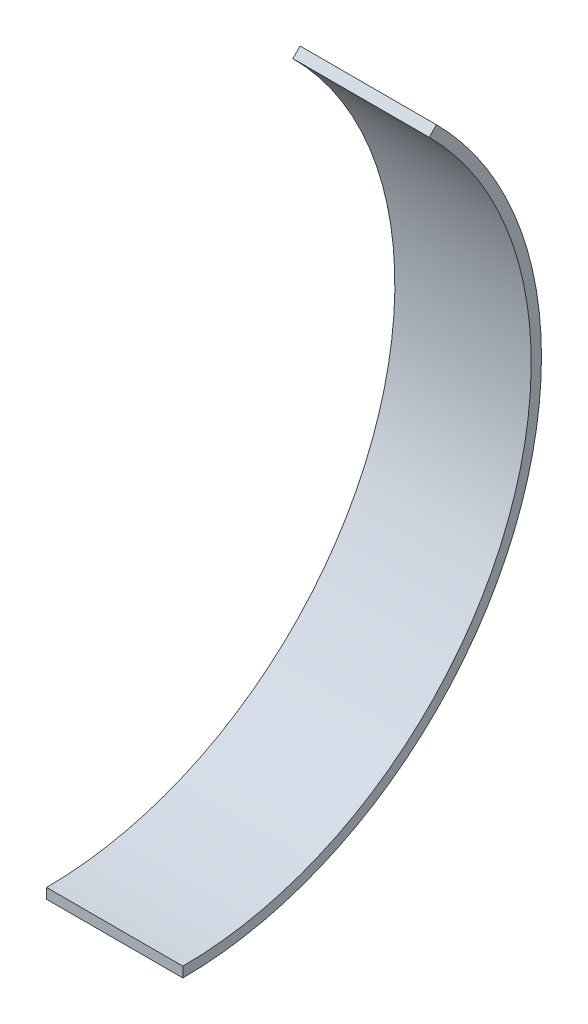
SolidWorks part; units mm, degrees
ref_plane "Front Plane" through (0, 0, 0) normal (0, 0, 1) x (1, 0, 0)
ref_plane "Top Plane" through (0, 0, 0) normal (0, 1, 0) x (1, 0, 0)
ref_plane "Right Plane" through (0, 0, 0) normal (1, 0, 0) x (0, 0, -1)
sketch "Sketch1" plane through (0, 0, 0) normal (0, 0, 1) x (1, 0, 0)
  line L0 (0, 0) -> (43.842, 0)
  line L1 (0, 112.014) -> (26.162, 112.014) construction
  dimension "D1" = 43.842
  dimension "D2" = 112.014
revolve "Revolve-Thin1" add sketch "Sketch1" angle 135 about L1
equation "\"FoamCore\" = \".2\""
equation "\"MDF\" = \".2\""
equation "\"GMaterial\"= \".2\""
equation "\"PVCMountDiameter\" = \"0.5in\""
equation "\"PVCMountDistanceToEdge\" = \"0.5\""
equation "\"PVCThickness\" = \"0.13in\""
equation "\"PVCDiameter\" = 1.5in"
equation "\"BaseWidth\" = \"8in\""
equation "\"BaseLength\" = \"10in\""
equation "\"BallDiameter\" = \"38mm\""
equation "\"BaseGap\" = \"4in\""
equation "\"FunnelTopDiameter\" = \"8in\""
equation "\"FunnelTopDepth\" = \"0.5in\""
equation "\"BallGap\" = \"0.1in\""
equation "\"FunnelLength\" = 3in"
equation "\"FunnelMaterial\" = 0.1in"
equation "\"FunnelLowerDiameter\" = 1.9in"
equation "\"FunnelDepth\" = 1.5in"
equation "\"FunnelBendLength\" = 2*pi*\"FunnelLowerDiameter\"/2*135"
equation "\"AmmoFeederLength\" = 1.5in + 76mm"
equation "\"WheelThickness\" = 0.5in"
equation "\"LauncherWheelDiameter\" = 76mm"
equation "\"MotorFrontLength\" = 0.95in"
equation "\"MotorBodyTotalLength\" = 2.03in"
equation "\"MotorFrontDiameter\" = 1.5in"
equation "\"MotorLowerDriveshaftDiameter\" = 0.46in"
equation "\"MotorLowerDriveshaftThickness\" = 0.25in"
equation "\"MotorFullDriveshaftLength\" = 0.78in"
equation "\"MotorDriveshaftDiameter\" = 0.23in"
equation "\"MotorDriveshaftFlatThickness\" = 0.2in"
equation "\"MotorRearDiameter\" = 31.9mm"
equation "\"MotorDriveshaftBottomToTop\" = 31.1mm"
equation "\"MotorFlatDriveshaftLength\" = 11.7mm"
equation "\"MotorDistanceBetweenLowerandTopHoles\" = 0.5in"
equation "\"MotorMountsDistanceFromEdge\" = 0.06in"
equation "\"MotorScrewMountDiameter\" = 0.1in"
equation "\"MotorScrewMountDepth\" = 0.13in"
equation "\"HBRidgeScrewHoleDeep\" = 0.18in"
equation "\"MotorMountWidth\" = \"1.61in\""
equation "\"MotorMountLength\" = \"1.58in\""
equation "\"MotorMountToEdgeGap\" = \"3.3mm\""
equation "\"MotorMountToInsideEdgeGap\" = \"6.5mm\""
equation "\"MotorMountToMountWidthGap\" = \"25.8mm\""
equation "\"MotorMountToMountLengthGap\" = \"20.5mm\""
equation "\"MotorMountMaterialThickness\" = 1.6mm"
equation "\"MotorMountBaseScrewholeDiameter\" = 3.8mm"
equation "\"MotorMountBaseDistancebetweenHoles\" = 0.8in"
equation "\"MotorMountHeight\" = 1.85in"
equation "\"HBridgeWidth\" = 2.25in"
equation "\"HBridgeLength\" = 1.40in"
equation "\"UnoWidth\" = 3.13in"
equation "\"UnoLength\" = 3.06in"
equation "\"BatteryWidth\" = 1.15in"
equation "\"BatteryLength\" = 3.86in"
equation "\"ScrewDiameter\" = 2.7mm"
equation "\"MotorMountFaceScrewtoBase\" = 0.46in"
equation "\"MotorMountFaceDistanceBetweenScrews\" = 0.95in"
equation "\"MotorMountFaceMiddletoEdge\" = 0.16in"
equation "\"MotorMountFaceBottomtoEdge\" = 0.42in"
equation "\"MotorMountCenterholeHeight\" = 1.04in"
equation "\"MotorMountCenterholetoEdge\" = 0.25in"
equation "\"MovingWheelDiameter\" = 76mm"
equation "\"MovingWheelThickness\" = 0.5in"
equation "\"BraceLength\" = 1in"
equation "\"BraceVerticalOffset\" = 3.5in"
equation "\"BraceHorizontalOffset\" = 2.5in"
equation "\"BaseToBaseDistance\" = 7in"
equation "\"PVCOutsideDiameter\" = \"PVCDiameter\" + 2*\"PVCThickness\""
equation "\"Distancebetweenwalls\" = 6in"
equation "\"Slidewidth\" = 0.3in"
equation "\"Slidelength\" = 0.8in"
equation "\"Bottomtofloor\" = 0.53in"
equation "\"tabdistance\" = 0.2in"
equation "\"tabwidth\" = 0.3in"
equation "\"ShooterWheelDiameter\"= 1.88in"
equation "\"ShooterWheelThick\"= 1.03in"
equation "\"ShooterRubberThick\"= 0.3in"
equation "\"D1@Sketch1\"=\"BallDiameter\" + 0.03in + \"MDF\""
equation "\"D2@Sketch1\"=\"ShooterWheelDiameter\"+\"ShooterWheelThick\"+\"PVCDiameter\""
equation "\"D3@Revolve-Thin1\"=\"3DMaterial\""
equation "\"3DMaterial\" = \"PVCThickness\""
